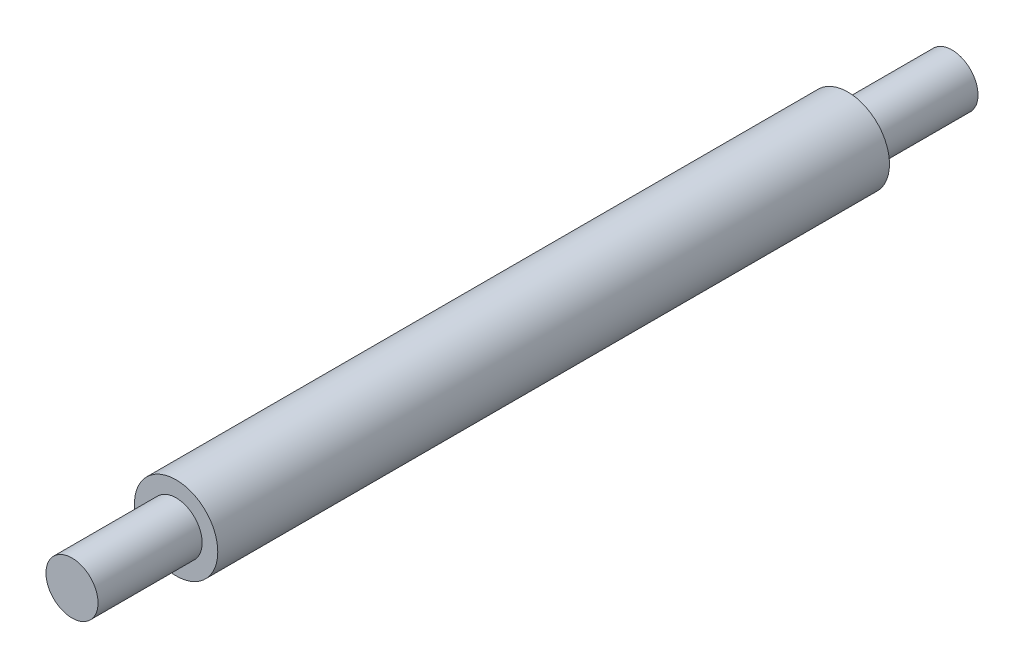
SolidWorks part; units mm, degrees
material "1060 Alloy"
ref_plane "Front Plane" through (0, 0, 0) normal (0, 0, 1) x (1, 0, 0)
ref_plane "Top Plane" through (0, 0, 0) normal (0, 1, 0) x (1, 0, 0)
ref_plane "Right Plane" through (0, 0, 0) normal (1, 0, 0) x (0, 0, -1)
sketch "Sketch1" plane through (0, 0, 0) normal (0, 0, 1) x (1, 0, 0)
  circle A0 centre (0, 0) radius 101.6
  dimension "D1" = 203.2
extrude "Boss-Extrude1" add sketch "Sketch1" along normal mid plane 1638.3
sketch "Sketch2" plane through (0, 0, 819.15) normal (0, 0, 1) x (1, 0, 0)
  circle A0 centre (0, 0) radius 63.5
  dimension "D1" = 127
extrude "Boss-Extrude2" add sketch "Sketch2" along normal blind 254
mirror "Mirror1" about plane through (0, 0, 0) normal (0, 0, 1) of "Boss-Extrude2"
